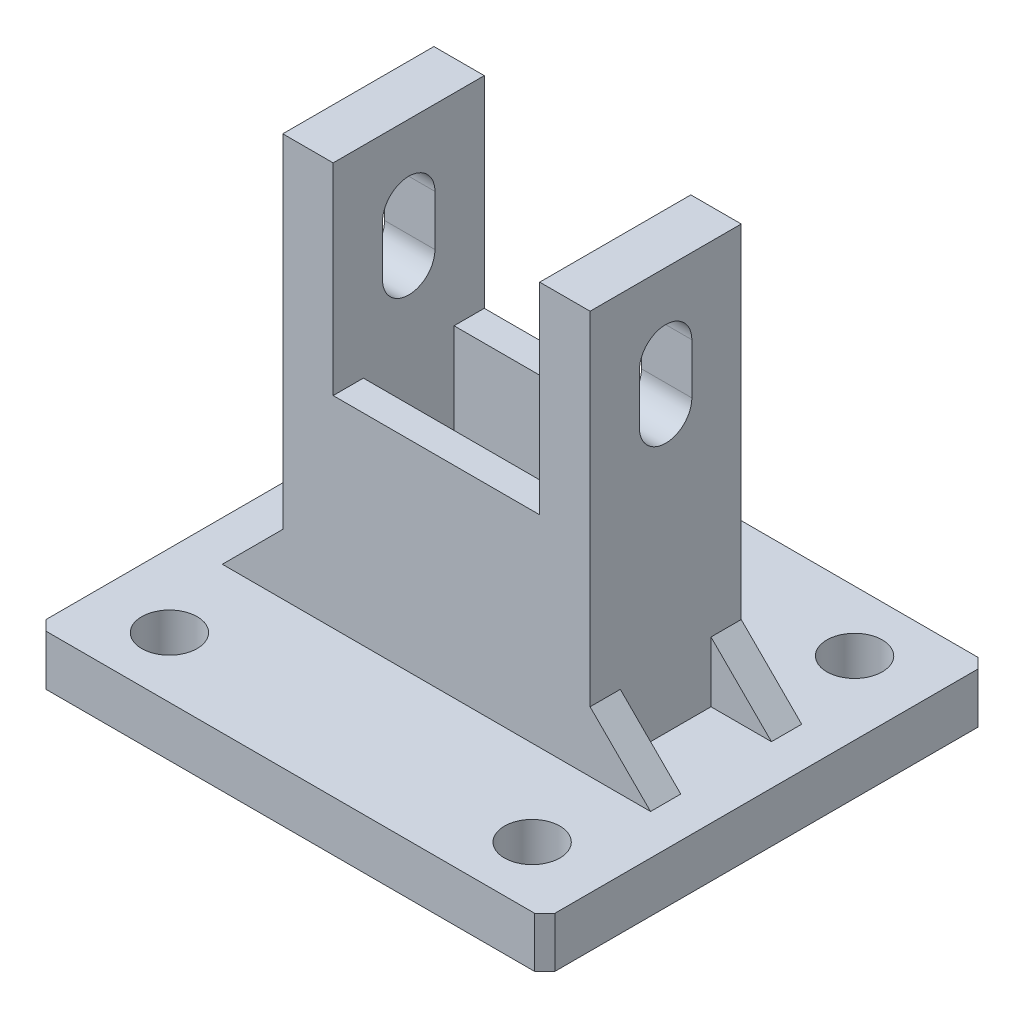
SolidWorks part; units mm, degrees
ref_plane "Front Plane" through (0, 0, 0) normal (0, 0, 1) x (1, 0, 0)
ref_plane "Top Plane" through (0, 0, 0) normal (0, 1, 0) x (1, 0, 0)
ref_plane "Right Plane" through (0, 0, 0) normal (1, 0, 0) x (0, 0, -1)
sketch "Sketch1" plane through (0, 0, 0) normal (0, 1, 0) x (1, 0, 0)
  line L1 (-18, 16) -> (18, 16) construction
  line L2 (-18, 16) -> (-18, -16) construction
  line L3 (-18, -16) -> (18, -16) construction
  line L4 (18, 16) -> (18, -16) construction
  line L5 (-18, 16) -> (18, -16) construction
  line L6 (-18, -16) -> (18, 16) construction
  line L7 (-25.25, 22) -> (25.25, 22)
  line L8 (-25.25, 22) -> (-25.25, -22)
  line L9 (-25.25, -22) -> (25.25, -22)
  line L10 (25.25, 22) -> (25.25, -22)
  line L11 (-25.25, 22) -> (25.25, -22) construction
  line L12 (-25.25, -22) -> (25.25, 22) construction
  circle A0 centre (-18, 16) radius 2.75
  circle A1 centre (18, 16) radius 2.75
  circle A2 centre (18, -16) radius 2.75
  circle A3 centre (-18, -16) radius 2.75
  point P0 (0, 0)
  point P10 (0, 0)
  dimension "D3" = 5.5
  dimension "D1" = 32
  dimension "D2" = 36
  dimension "D4" = 50.5
  dimension "D5" = 44
extrude "Boss-Extrude1" add sketch "Sketch1" along normal blind 5
sketch "Sketch3" plane through (0, 0, 22) normal (0, 0, 1) x (1, 0, 0)
  line L0 (-25.25, 5) -> (25.25, 5) construction
  line L1 (-15.25, 5) -> (-10.25, 5)
  line L2 (-15.25, 5) -> (-15.25, 45)
  line L3 (-15.25, 45) -> (-10.25, 45)
  line L4 (-10.25, 5) -> (-10.25, 45)
  line L6 (10.25, 5) -> (15.25, 5)
  line L7 (10.25, 5) -> (10.25, 45)
  line L8 (10.25, 45) -> (15.25, 45)
  line L9 (15.25, 5) -> (15.25, 45)
  line L10 (0, 0) -> (0, -8.4132) construction
  dimension "D1" = 5
  dimension "D2" = 20.5
  dimension "D3" = 40
extrude "Boss-Extrude2" add sketch "Sketch3" against normal blind 15 from offset 14.5 offset against normal yes
sketch "Sketch4" plane through (15.25, 0, 0) normal (1, 0, 0) x (0, 0, -1)
  line L0 (0, 37.5) -> (0, 32.5) construction
  line L1 (2.6, 37.5) -> (2.6, 32.5)
  line L2 (-2.6, 37.5) -> (-2.6, 32.5)
  line L3 (7.5, 45) -> (-7.5, 45) construction
  arc A0 (2.6, 37.5) -> (-2.6, 37.5) centre (0, 37.5) ccw
  arc A1 (-2.6, 32.5) -> (2.6, 32.5) centre (0, 32.5) ccw
  point P3 (0, 35)
  dimension "D2" = 2.6
  dimension "D1" = 5
  dimension "D3" = 10
extrude "Cut-Extrude1" cut sketch "Sketch4" against normal up to surface (30.5 mm away) up to face at (-15.25, 25, 0)
sketch "Sketch5" plane through (0, 0, 7.5) normal (0, 0, 1) x (1, 0, 0)
  line L0 (15.25, 11) -> (21.25, 5)
  line L1 (15.25, 5) -> (15.25, 45) construction
  line L2 (-25.25, 5) -> (25.25, 5) construction
  line L3 (21.25, 5) -> (15.25, 5)
  line L4 (15.25, 5) -> (15.25, 11)
  line L5 (0, -1.6344) -> (0, 7.9357) construction
  line L6 (-21.25, 5) -> (-15.25, 5)
  line L7 (-15.25, 11) -> (-21.25, 5)
  line L8 (-15.25, 5) -> (-15.25, 11)
  line L17 (-10.25, 5) -> (-10.25, 45) construction
  line L18 (-10.25, 25) -> (10.25, 25)
  line L19 (-10.25, 25) -> (-10.25, 5)
  line L20 (-10.25, 5) -> (10.25, 5)
  line L21 (10.25, 25) -> (10.25, 5)
  dimension "D1" = 45
  dimension "D2" = 6
  dimension "D3" = 20
extrude "Boss-Extrude3" add sketch "Sketch5" against normal blind 3
ref_plane "Plane1" through (0, 0, 0) normal (0, 0, -1) x (-1, 0, 0)
mirror "Mirror1" about plane through (0, 0, 0) normal (0, 0, -1) of "Boss-Extrude3"
chamfer "Chamfer2" distance 1 angle 45 4 edges at (25.25, 2.5, 22) (-25.25, 2.5, -22) (25.25, 2.5, -22) (-25.25, 2.5, 22)
